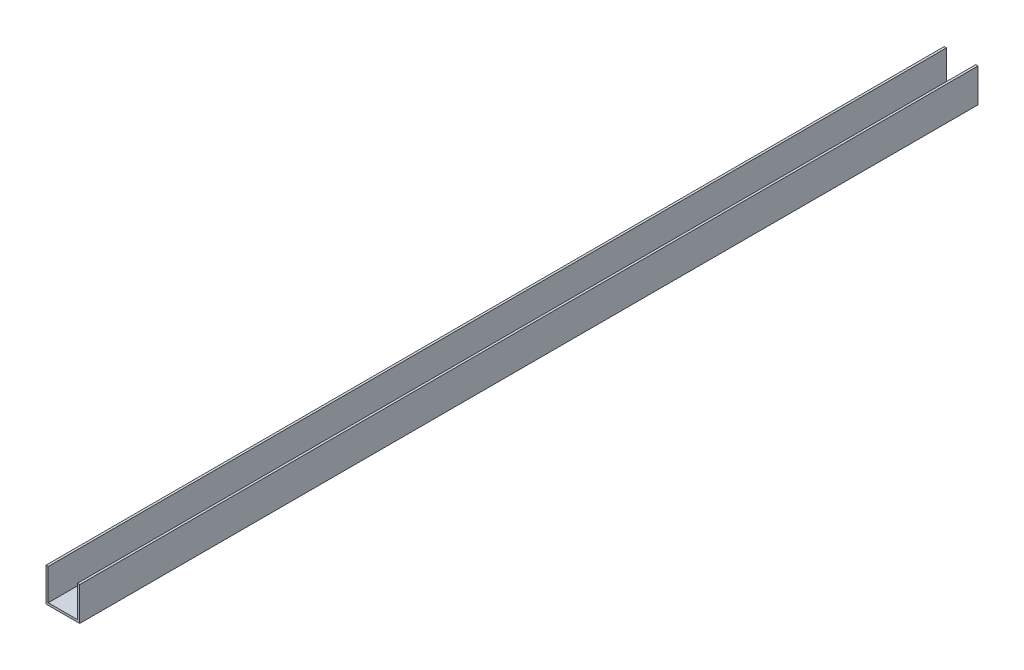
SolidWorks part; units mm, degrees
ref_plane "Спереди" through (0, 0, 0) normal (0, 0, 1) x (1, 0, 0)
ref_plane "Сверху" through (0, 0, 0) normal (0, 1, 0) x (1, 0, 0)
ref_plane "Справа" through (0, 0, 0) normal (1, 0, 0) x (0, 0, -1)
sketch "Эскиз1" plane through (0, 0, 0) normal (0, 0, 1) x (1, 0, 0)
  line L0 (-7, 0) -> (7, 0)
  line L1 (7, 0) -> (7, 14.5)
  line L2 (0, -8.3137) -> (0, 17.7347) construction
  line L3 (-7, 0) -> (-7, 14.5)
  point P7 (0, 0)
  dimension "D1" = 7
  dimension "D2" = 14.5
surface "Поверхность-Вытянуть1" sketch "Эскиз1" parameters "D1"=400
thicken "Придать толщину1" surfaces to thicken 103 thickness 0.5 thickness side both sides parameters "D1"=0.5
